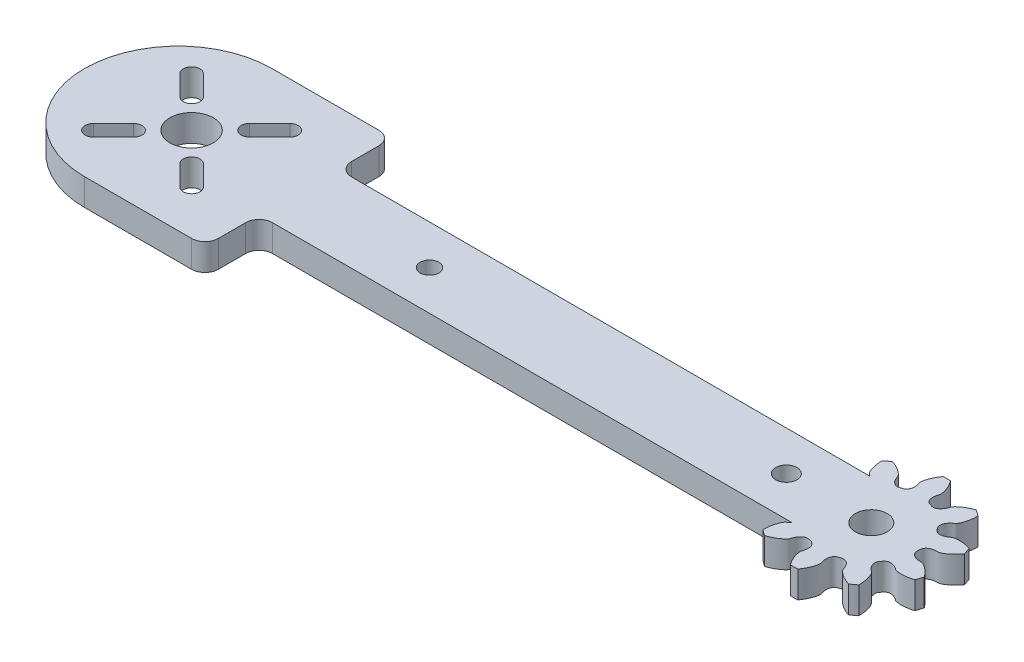
SolidWorks part; units mm, degrees
material "Thornel VCB-20 Carbon Cloth"
ref_plane "Front Plane" through (0, 0, 0) normal (0, 0, 1) x (1, 0, 0)
ref_plane "Top Plane" through (0, 0, 0) normal (0, 1, 0) x (1, 0, 0)
ref_plane "Right Plane" through (0, 0, 0) normal (1, 0, 0) x (0, 0, -1)
sketch "Sketch1" plane through (0, 0, 0) normal (0, 1, 0) x (1, 0, 0)
  line L0 (-58.0134, 7.2134) -> (-43.5866, -7.2134) construction
  line L1 (-50.8, 14) -> (-36.8, 14)
  line L2 (-50.8, 14) -> (-50.8, -14) construction
  line L3 (-50.8, -14) -> (-36.8, -14)
  line L7 (-58.4887, -7.6887) -> (-43.1113, 7.6887) construction
  line L8 (-58.1362, 7.3362) -> (-55.131, 4.331) construction
  line L9 (-57.2523, 8.2201) -> (-54.2471, 5.2149)
  line L10 (-59.0201, 6.4523) -> (-56.0149, 3.4471)
  line L11 (-43.4638, 7.3362) -> (-46.469, 4.331) construction
  line L12 (-42.5799, 6.4523) -> (-45.5851, 3.4471)
  line L13 (-44.3477, 8.2201) -> (-47.3529, 5.2149)
  line L14 (-43.4638, -7.3362) -> (-46.469, -4.331) construction
  line L15 (-44.3477, -8.2201) -> (-47.3529, -5.2149)
  line L16 (-42.5799, -6.4523) -> (-45.5851, -3.4471)
  line L17 (-58.1362, -7.3362) -> (-55.131, -4.331) construction
  line L18 (-59.0201, -6.4523) -> (-56.0149, -3.4471)
  line L19 (-57.2523, -8.2201) -> (-54.2471, -5.2149)
  line L21 (-34.8, 7.9146) -> (-34.8, 12)
  line L24 (-34.8, -12) -> (-34.8, -7.9146)
  line L32 (-32.8, 5.9146) -> (50.8, 5.9146)
  line L33 (-32.8, -5.9146) -> (50.8, -5.9146)
  line L34 (-50.8, 0) -> (50.8, 0) construction
  line L35 (-50.8, 14) -> (-52.8, 14)
  line L36 (-50.8, -14) -> (-52.8, -14)
  circle A2 centre (-50.8, 0) radius 3.25
  arc A3 (-57.2523, 8.2201) -> (-59.0201, 6.4523) centre (-58.1362, 7.3362) ccw
  arc A4 (-56.0149, 3.4471) -> (-54.2471, 5.2149) centre (-55.131, 4.331) ccw
  arc A5 (-42.5799, 6.4523) -> (-44.3477, 8.2201) centre (-43.4638, 7.3362) ccw
  arc A6 (-47.3529, 5.2149) -> (-45.5851, 3.4471) centre (-46.469, 4.331) ccw
  arc A7 (-44.3477, -8.2201) -> (-42.5799, -6.4523) centre (-43.4638, -7.3362) ccw
  arc A8 (-45.5851, -3.4471) -> (-47.3529, -5.2149) centre (-46.469, -4.331) ccw
  arc A9 (-59.0201, -6.4523) -> (-57.2523, -8.2201) centre (-58.1362, -7.3362) ccw
  arc A10 (-54.2471, -5.2149) -> (-56.0149, -3.4471) centre (-55.131, -4.331) ccw
  circle A11 centre (50.8, 0) radius 2.3813
  arc A12 (-34.8, -7.9146) -> (-32.8, -5.9146) centre (-32.8, -7.9146) cw
  arc A13 (-32.8, 5.9146) -> (-34.8, 7.9146) centre (-32.8, 7.9146) cw
  arc A14 (-36.8, -14) -> (-34.8, -12) centre (-36.8, -12) ccw
  arc A15 (-34.8, 12) -> (-36.8, 14) centre (-36.8, 12) ccw
  arc A16 (50.8, 5.9146) -> (50.8, -5.9146) centre (50.8, 0) cw
  arc A17 (-52.8, -14) -> (-52.8, 14) centre (-52.8, 0) cw
  circle A18 centre (-15.24, 0) radius 1.397
  point P0 (0, 0)
  point P12 (-50.8, 0)
  point P14 (-50.8, 0)
  point P17 (-56.6336, 5.8336)
  point P27 (-44.9664, 5.8336)
  point P34 (-44.9664, -5.8336)
  point P41 (-56.6336, -5.8336)
  point P46 (-50.8, 0)
  point P53 (-34.8, -7)
  point P56 (-34.8, 7)
  point P59 (-34.8, -14)
  point P62 (-34.8, 14)
  dimension "D3" = 6.5
  dimension "D6" = 8.25
  dimension "D10" = 4.7625
  dimension "D17" = 2
  dimension "D18" = 2
  dimension "D16" = 5.9146
  dimension "D2" = 14
  dimension "D21" = 2.794
  dimension "D22" = 66.04
  dimension "D4" = 45
  dimension "D5" = 45
  dimension "D7" = 4.25
  dimension "D8" = 2.5
  dimension "D11" = 16
  dimension "D12" = 16
  dimension "D13" = 7
  dimension "D14" = 7
  dimension "D15" = 101.6
  dimension "D19" = 50.8
  dimension "D20" = 2
  dimension "D9" = 4
extrude "Boss-Extrude1" add sketch "Sketch1" along normal blind 4
sketch "Sketch2" plane through (0, 0, 0) normal (0, -1, 0) x (1, 0, 0)
  circle A0 centre (38.1, 0) radius 1.5875
  circle A1 centre (50.8, 0) radius 2.3813 construction
  dimension "D1" = 3.175
  dimension "D2" = 12.7
extrude "Cut-Extrude1" cut sketch "Sketch2" against normal blind 10
sketch "Sketch3" plane through (0, 0, 0) normal (0, -1, 0) x (1, 0, 0)
  arc A0 (40.0686, 4.1334) -> (39.7228, 3.0691) centre (50.7532, 0.0734) ccw
  arc A1 (39.7228, -2.9222) -> (40.0686, -3.9866) centre (50.7532, 0.0734) ccw
  arc A2 (43.5902, -8.8336) -> (44.4956, -9.4915) centre (50.7532, 0.0734) ccw
  arc A3 (50.1937, -11.3429) -> (51.3128, -11.3429) centre (50.7532, 0.0734) ccw
  arc A4 (57.0109, -9.4915) -> (57.9163, -8.8336) centre (50.7532, 0.0734) ccw
  arc A5 (61.4378, -3.9866) -> (61.7837, -2.9222) centre (50.7532, 0.0734) ccw
  arc A6 (61.7837, 3.0691) -> (61.4378, 4.1334) centre (50.7532, 0.0734) ccw
  arc A7 (57.9163, 8.9805) -> (57.0109, 9.6383) centre (50.7532, 0.0734) ccw
  arc A8 (51.3128, 11.4897) -> (50.1937, 11.4897) centre (50.7532, 0.0734) ccw
  arc A9 (44.4956, 9.6383) -> (43.5902, 8.9805) centre (50.7532, 0.0734) ccw
  circle A10 centre (50.7532, 0.0734) radius 4.0735
  spline S0 degree 3 poles (39.7228, 3.0691) (39.8092, 2.9516) (39.9522, 2.7692) (40.1581, 2.5337) (40.3253, 2.3574) (40.4889, 2.1982) (40.6479, 2.0557) (40.8012, 1.929) (40.9477, 1.8176) (41.0866, 1.7206) (41.2169, 1.6373) (41.3377, 1.5668) (41.4483, 1.508) (41.5479, 1.4604) (41.6357, 1.4219) (41.7286, 1.388) (41.8483, 1.3381) (41.9663, 1.3631) (42.0573, 1.3611) (42.1051, 1.3604) (42.1524, 1.3587) (42.1991, 1.3562) (42.2901, 1.3499) (42.4086, 1.3365) (42.5525, 1.3107) (42.6765, 1.2808) (42.7956, 1.2439) (42.9096, 1.1998) (43.0187, 1.148) (43.111, 1.0946) (43.1879, 1.0422) (43.2512, 0.9929) (43.3116, 0.939) (43.3686, 0.8801) (43.4217, 0.816) (43.4703, 0.7464) (43.5135, 0.6712) (43.5502, 0.5907) (43.5794, 0.5053) (43.5966, 0.4309) (43.6057, 0.3699) (43.61, 0.3234) (43.6116, 0.2818) (43.6116, 0.1985) (43.6077, 0.0734) (43.6116, -0.0516) (43.6116, -0.135) (43.61, -0.1766) (43.6057, -0.223) (43.5966, -0.2841) (43.5794, -0.3584) (43.5502, -0.4439) (43.5135, -0.5244) (43.4703, -0.5995) (43.4217, -0.6691) (43.3686, -0.7333) (43.3116, -0.7921) (43.2512, -0.846) (43.1775, -0.9035) (43.0885, -0.9621) (42.9829, -1.0193) (42.8722, -1.0685) (42.7564, -1.1101) (42.6357, -1.1447) (42.5101, -1.1723) (42.3795, -1.1932) (42.2753, -1.2041) (42.1991, -1.2094) (42.1524, -1.2118) (42.1051, -1.2136) (42.0573, -1.2143) (41.9663, -1.2163) (41.8483, -1.1912) (41.7286, -1.2412) (41.6357, -1.2751) (41.5479, -1.3135) (41.4483, -1.3612) (41.3377, -1.4199) (41.2169, -1.4905) (41.0866, -1.5738) (40.9477, -1.6708) (40.8012, -1.7822) (40.6479, -1.9088) (40.4889, -2.0514) (40.3253, -2.2105) (40.1581, -2.3869) (39.9522, -2.6224) (39.8092, -2.8048) (39.7228, -2.9222) knots 0.011285 0.011285 0.011285 0.011285 0.051699 0.075508 0.097957 0.119044 0.138772 0.157139 0.174145 0.189791 0.204076 0.217001 0.228565 0.238769 0.247612 0.255095 0.266315 0.282698 0.287164 0.291581 0.295951 0.300274 0.304552 0.321228 0.333312 0.345077 0.356567 0.36784 0.378959 0.390003 0.397367 0.404766 0.412228 0.419785 0.427466 0.435294 0.44329 0.45146 0.4598 0.46829 0.472581 0.476895 0.481226 0.484109 0.5 0.515891 0.518774 0.523105 0.527419 0.53171 0.5402 0.54854 0.55671 0.564706 0.572534 0.580215 0.587772 0.595234 0.602633 0.613675 0.624735 0.635897 0.647236 0.658812 0.670678 0.682878 0.695448 0.699726 0.704049 0.708419 0.712836 0.717302 0.733685 0.744905 0.752388 0.761231 0.771435 0.782999 0.795924 0.810209 0.825855 0.842861 0.861228 0.880956 0.902043 0.924492 0.948301 0.988715 0.988715 0.988715 0.988715 weights 1 1 1 1 1 1 1 1 1 1 1 1 1 1 1 1 1 1 1 1 1 1 1 1 1 1 1 1 1 1 1 1 1 1 1 1 1 1 1 1 1 1 1 1 1 1 1 1 1 1 1 1 1 1 1 1 1 1 1 1 1 1 1 1 1 1 1 1 1 1 1 1 1 1 1 1 1 1 1 1 1 1 1 1 1 1 1 1 1
  spline S1 degree 3 poles (40.0686, -3.9866) (40.2075, -4.0308) (40.4305, -4.0943) (40.7354, -4.1638) (40.9743, -4.2082) (41.2003, -4.2408) (41.4127, -4.2627) (41.6112, -4.275) (41.7952, -4.279) (41.9646, -4.2758) (42.1189, -4.2667) (42.2581, -4.2527) (42.3821, -4.2353) (42.4907, -4.2153) (42.5844, -4.1947) (42.6795, -4.1676) (42.8057, -4.1376) (42.8864, -4.048) (42.9611, -3.9961) (43.0002, -3.9686) (43.0395, -3.9423) (43.0788, -3.9168) (43.1561, -3.8684) (43.2598, -3.8096) (43.3915, -3.7458) (43.5094, -3.6972) (43.6273, -3.657) (43.7456, -3.6257) (43.8642, -3.6035) (43.9703, -3.5924) (44.0634, -3.5896) (44.1435, -3.5923) (44.2241, -3.6004) (44.3048, -3.6145) (44.3855, -3.6352) (44.4657, -3.6629) (44.5448, -3.6984) (44.6218, -3.7419) (44.6957, -3.7939) (44.7533, -3.8439) (44.7965, -3.888) (44.8273, -3.923) (44.853, -3.9557) (44.902, -4.0232) (44.9724, -4.1266) (45.049, -4.2255) (45.098, -4.2929) (45.1212, -4.3275) (45.145, -4.3677) (45.1735, -4.4223) (45.2033, -4.4926) (45.2299, -4.5789) (45.2475, -4.6656) (45.2568, -4.7518) (45.2584, -4.8367) (45.2531, -4.9198) (45.2416, -5.0009) (45.2244, -5.08) (45.1985, -5.1698) (45.161, -5.2696) (45.1092, -5.3779) (45.0485, -5.4828) (44.9794, -5.5845) (44.902, -5.6834) (44.8166, -5.7796) (44.7233, -5.8732) (44.6453, -5.9433) (44.5868, -5.9924) (44.5504, -6.0218) (44.5132, -6.051) (44.4749, -6.0797) (44.4025, -6.1348) (44.2923, -6.1839) (44.2249, -6.2946) (44.1696, -6.3767) (44.1211, -6.4594) (44.0686, -6.5565) (44.0137, -6.669) (43.9574, -6.7971) (43.901, -6.9411) (43.8456, -7.1012) (43.7925, -7.2775) (43.743, -7.47) (43.6981, -7.6788) (43.6593, -7.9038) (43.6277, -8.1447) (43.5996, -8.4562) (43.5911, -8.6878) (43.5902, -8.8336) knots 0.011285 0.011285 0.011285 0.011285 0.051699 0.075508 0.097957 0.119044 0.138772 0.157139 0.174145 0.189791 0.204076 0.217001 0.228565 0.238769 0.247612 0.255095 0.266315 0.282698 0.287164 0.291581 0.295951 0.300274 0.304552 0.321228 0.333312 0.345077 0.356567 0.36784 0.378959 0.390003 0.397367 0.404766 0.412228 0.419785 0.427466 0.435294 0.44329 0.45146 0.4598 0.46829 0.472581 0.476895 0.481226 0.484109 0.5 0.515891 0.518774 0.523105 0.527419 0.53171 0.5402 0.54854 0.55671 0.564706 0.572534 0.580215 0.587772 0.595234 0.602633 0.613675 0.624735 0.635897 0.647236 0.658812 0.670678 0.682878 0.695448 0.699726 0.704049 0.708419 0.712836 0.717302 0.733685 0.744905 0.752388 0.761231 0.771435 0.782999 0.795924 0.810209 0.825855 0.842861 0.861228 0.880956 0.902043 0.924492 0.948301 0.988715 0.988715 0.988715 0.988715 weights 1 1 1 1 1 1 1 1 1 1 1 1 1 1 1 1 1 1 1 1 1 1 1 1 1 1 1 1 1 1 1 1 1 1 1 1 1 1 1 1 1 1 1 1 1 1 1 1 1 1 1 1 1 1 1 1 1 1 1 1 1 1 1 1 1 1 1 1 1 1 1 1 1 1 1 1 1 1 1 1 1 1 1 1 1 1 1 1 1
  spline S2 degree 3 poles (44.4956, -9.4915) (44.634, -9.4456) (44.8517, -9.3659) (45.1392, -9.2429) (45.3586, -9.1384) (45.5606, -9.0319) (45.7453, -8.9248) (45.9131, -8.8181) (46.0643, -8.7132) (46.1995, -8.6111) (46.319, -8.5129) (46.4234, -8.4198) (46.5135, -8.3328) (46.5896, -8.2528) (46.6532, -8.1811) (46.7142, -8.1033) (46.7987, -8.0048) (46.8113, -7.8849) (46.8413, -7.799) (46.8568, -7.7537) (46.8731, -7.7093) (46.8898, -7.6656) (46.924, -7.5811) (46.9733, -7.4725) (47.0423, -7.3436) (47.1091, -7.2349) (47.181, -7.1331) (47.2582, -7.0382) (47.3411, -6.9505) (47.4204, -6.8792) (47.4941, -6.8222) (47.5605, -6.7773) (47.6304, -6.7365) (47.704, -6.7005) (47.7815, -6.6698) (47.8627, -6.6451) (47.9475, -6.6273) (48.0354, -6.6172) (48.1257, -6.6158) (48.2017, -6.6225) (48.2626, -6.6327) (48.3081, -6.6429) (48.3481, -6.6543) (48.4274, -6.68) (48.5451, -6.7224) (48.6653, -6.7573) (48.7445, -6.7831) (48.7836, -6.7974) (48.8264, -6.8159) (48.8817, -6.8434) (48.9471, -6.8827) (49.0193, -6.9369) (49.0846, -6.9967) (49.1427, -7.061) (49.1939, -7.1287) (49.2384, -7.1991) (49.2768, -7.2715) (49.3094, -7.3455) (49.3413, -7.4334) (49.3695, -7.5362) (49.3913, -7.6543) (49.4038, -7.7748) (49.4077, -7.8977) (49.4033, -8.0232) (49.3907, -8.1512) (49.3702, -8.2818) (49.3484, -8.3844) (49.3299, -8.4585) (49.3178, -8.5037) (49.3048, -8.5492) (49.2907, -8.5949) (49.2645, -8.682) (49.2042, -8.7864) (49.2147, -8.9157) (49.2183, -9.0146) (49.2277, -9.11) (49.2422, -9.2194) (49.2639, -9.3427) (49.2937, -9.4794) (49.3327, -9.6291) (49.382, -9.7911) (49.4426, -9.9649) (49.5157, -10.1499) (49.6022, -10.3451) (49.703, -10.55) (49.819, -10.7635) (49.9794, -11.032) (50.1087, -11.2244) (50.1937, -11.3429) knots 0.011285 0.011285 0.011285 0.011285 0.051699 0.075508 0.097957 0.119044 0.138772 0.157139 0.174145 0.189791 0.204076 0.217001 0.228565 0.238769 0.247612 0.255095 0.266315 0.282698 0.287164 0.291581 0.295951 0.300274 0.304552 0.321228 0.333312 0.345077 0.356567 0.36784 0.378959 0.390003 0.397367 0.404766 0.412228 0.419785 0.427466 0.435294 0.44329 0.45146 0.4598 0.46829 0.472581 0.476895 0.481226 0.484109 0.5 0.515891 0.518774 0.523105 0.527419 0.53171 0.5402 0.54854 0.55671 0.564706 0.572534 0.580215 0.587772 0.595234 0.602633 0.613675 0.624735 0.635897 0.647236 0.658812 0.670678 0.682878 0.695448 0.699726 0.704049 0.708419 0.712836 0.717302 0.733685 0.744905 0.752388 0.761231 0.771435 0.782999 0.795924 0.810209 0.825855 0.842861 0.861228 0.880956 0.902043 0.924492 0.948301 0.988715 0.988715 0.988715 0.988715 weights 1 1 1 1 1 1 1 1 1 1 1 1 1 1 1 1 1 1 1 1 1 1 1 1 1 1 1 1 1 1 1 1 1 1 1 1 1 1 1 1 1 1 1 1 1 1 1 1 1 1 1 1 1 1 1 1 1 1 1 1 1 1 1 1 1 1 1 1 1 1 1 1 1 1 1 1 1 1 1 1 1 1 1 1 1 1 1 1 1
  spline S3 degree 3 poles (51.3128, -11.3429) (51.3978, -11.2244) (51.527, -11.032) (51.6874, -10.7635) (51.8035, -10.55) (51.9043, -10.3451) (51.9907, -10.1499) (52.0638, -9.9649) (52.1245, -9.7911) (52.1738, -9.6291) (52.2128, -9.4794) (52.2425, -9.3427) (52.2642, -9.2194) (52.2788, -9.11) (52.2882, -9.0146) (52.2917, -8.9157) (52.3022, -8.7864) (52.242, -8.682) (52.2157, -8.5949) (52.2016, -8.5492) (52.1887, -8.5037) (52.1766, -8.4585) (52.1545, -8.37) (52.1306, -8.2531) (52.1106, -8.1083) (52.1008, -7.9811) (52.0991, -7.8565) (52.1058, -7.7343) (52.1213, -7.6146) (52.1436, -7.5104) (52.1697, -7.421) (52.197, -7.3455) (52.2296, -7.2715) (52.268, -7.1991) (52.3126, -7.1287) (52.3637, -7.061) (52.4219, -6.9967) (52.4871, -6.9369) (52.5593, -6.8827) (52.6248, -6.8434) (52.68, -6.8159) (52.7229, -6.7974) (52.7619, -6.7831) (52.8412, -6.7573) (52.9613, -6.7224) (53.079, -6.68) (53.1583, -6.6543) (53.1983, -6.6429) (53.2439, -6.6327) (53.3047, -6.6225) (53.3807, -6.6158) (53.471, -6.6172) (53.559, -6.6273) (53.6438, -6.6451) (53.725, -6.6698) (53.8024, -6.7005) (53.876, -6.7365) (53.9459, -6.7773) (54.0234, -6.8297) (54.1066, -6.8962) (54.1936, -6.9789) (54.2746, -7.0691) (54.35, -7.1663) (54.4201, -7.2704) (54.4853, -7.3813) (54.5455, -7.499) (54.588, -7.5948) (54.6166, -7.6656) (54.6334, -7.7093) (54.6497, -7.7537) (54.6651, -7.799) (54.6951, -7.8849) (54.7077, -8.0048) (54.7922, -8.1033) (54.8532, -8.1811) (54.9169, -8.2528) (54.993, -8.3328) (55.083, -8.4198) (55.1875, -8.5129) (55.307, -8.6111) (55.4421, -8.7132) (55.5934, -8.8181) (55.7612, -8.9248) (55.9459, -9.0319) (56.1478, -9.1384) (56.3672, -9.2429) (56.6548, -9.3659) (56.8725, -9.4456) (57.0109, -9.4915) knots 0.011285 0.011285 0.011285 0.011285 0.051699 0.075508 0.097957 0.119044 0.138772 0.157139 0.174145 0.189791 0.204076 0.217001 0.228565 0.238769 0.247612 0.255095 0.266315 0.282698 0.287164 0.291581 0.295951 0.300274 0.304552 0.321228 0.333312 0.345077 0.356567 0.36784 0.378959 0.390003 0.397367 0.404766 0.412228 0.419785 0.427466 0.435294 0.44329 0.45146 0.4598 0.46829 0.472581 0.476895 0.481226 0.484109 0.5 0.515891 0.518774 0.523105 0.527419 0.53171 0.5402 0.54854 0.55671 0.564706 0.572534 0.580215 0.587772 0.595234 0.602633 0.613675 0.624735 0.635897 0.647236 0.658812 0.670678 0.682878 0.695448 0.699726 0.704049 0.708419 0.712836 0.717302 0.733685 0.744905 0.752388 0.761231 0.771435 0.782999 0.795924 0.810209 0.825855 0.842861 0.861228 0.880956 0.902043 0.924492 0.948301 0.988715 0.988715 0.988715 0.988715 weights 1 1 1 1 1 1 1 1 1 1 1 1 1 1 1 1 1 1 1 1 1 1 1 1 1 1 1 1 1 1 1 1 1 1 1 1 1 1 1 1 1 1 1 1 1 1 1 1 1 1 1 1 1 1 1 1 1 1 1 1 1 1 1 1 1 1 1 1 1 1 1 1 1 1 1 1 1 1 1 1 1 1 1 1 1 1 1 1 1
  spline S4 degree 3 poles (57.9163, -8.8336) (57.9154, -8.6878) (57.9068, -8.4562) (57.8788, -8.1447) (57.8471, -7.9038) (57.8083, -7.6788) (57.7635, -7.47) (57.7139, -7.2775) (57.6608, -7.1012) (57.6055, -6.9411) (57.549, -6.7971) (57.4928, -6.669) (57.4379, -6.5565) (57.3853, -6.4594) (57.3368, -6.3767) (57.2816, -6.2946) (57.2141, -6.1839) (57.1039, -6.1348) (57.0315, -6.0797) (56.9932, -6.051) (56.956, -6.0218) (56.9197, -5.9924) (56.8498, -5.9338) (56.7618, -5.8533) (56.6605, -5.7478) (56.5778, -5.6507) (56.5031, -5.5509) (56.4368, -5.4482) (56.379, -5.3422) (56.3357, -5.2448) (56.3042, -5.1571) (56.282, -5.08) (56.2649, -5.0009) (56.2534, -4.9198) (56.2481, -4.8367) (56.2497, -4.7518) (56.2589, -4.6656) (56.2765, -4.5789) (56.3031, -4.4926) (56.3329, -4.4223) (56.3615, -4.3677) (56.3852, -4.3275) (56.4084, -4.2929) (56.4574, -4.2255) (56.5341, -4.1266) (56.6044, -4.0232) (56.6534, -3.9557) (56.6791, -3.923) (56.71, -3.888) (56.7532, -3.8439) (56.8108, -3.7939) (56.8846, -3.7419) (56.9617, -3.6984) (57.0408, -3.6629) (57.121, -3.6352) (57.2017, -3.6145) (57.2824, -3.6004) (57.3629, -3.5923) (57.4564, -3.5892) (57.5628, -3.594) (57.6818, -3.6098) (57.8003, -3.6351) (57.9184, -3.6695) (58.0364, -3.7125) (58.1543, -3.7639) (58.2722, -3.8238) (58.3629, -3.8763) (58.4277, -3.9168) (58.4669, -3.9423) (58.5062, -3.9686) (58.5453, -3.9961) (58.6201, -4.048) (58.7008, -4.1376) (58.827, -4.1676) (58.9221, -4.1947) (59.0157, -4.2153) (59.1243, -4.2353) (59.2483, -4.2527) (59.3875, -4.2667) (59.5419, -4.2758) (59.7112, -4.279) (59.8953, -4.275) (60.0937, -4.2627) (60.3062, -4.2408) (60.5321, -4.2082) (60.771, -4.1638) (61.076, -4.0943) (61.2989, -4.0308) (61.4378, -3.9866) knots 0.011285 0.011285 0.011285 0.011285 0.051699 0.075508 0.097957 0.119044 0.138772 0.157139 0.174145 0.189791 0.204076 0.217001 0.228565 0.238769 0.247612 0.255095 0.266315 0.282698 0.287164 0.291581 0.295951 0.300274 0.304552 0.321228 0.333312 0.345077 0.356567 0.36784 0.378959 0.390003 0.397367 0.404766 0.412228 0.419785 0.427466 0.435294 0.44329 0.45146 0.4598 0.46829 0.472581 0.476895 0.481226 0.484109 0.5 0.515891 0.518774 0.523105 0.527419 0.53171 0.5402 0.54854 0.55671 0.564706 0.572534 0.580215 0.587772 0.595234 0.602633 0.613675 0.624735 0.635897 0.647236 0.658812 0.670678 0.682878 0.695448 0.699726 0.704049 0.708419 0.712836 0.717302 0.733685 0.744905 0.752388 0.761231 0.771435 0.782999 0.795924 0.810209 0.825855 0.842861 0.861228 0.880956 0.902043 0.924492 0.948301 0.988715 0.988715 0.988715 0.988715 weights 1 1 1 1 1 1 1 1 1 1 1 1 1 1 1 1 1 1 1 1 1 1 1 1 1 1 1 1 1 1 1 1 1 1 1 1 1 1 1 1 1 1 1 1 1 1 1 1 1 1 1 1 1 1 1 1 1 1 1 1 1 1 1 1 1 1 1 1 1 1 1 1 1 1 1 1 1 1 1 1 1 1 1 1 1 1 1 1 1
  spline S5 degree 3 poles (61.7837, -2.9222) (61.6973, -2.8048) (61.5542, -2.6224) (61.3484, -2.3869) (61.1812, -2.2105) (61.0175, -2.0514) (60.8586, -1.9088) (60.7053, -1.7822) (60.5587, -1.6708) (60.4198, -1.5738) (60.2896, -1.4905) (60.1687, -1.4199) (60.0582, -1.3612) (59.9586, -1.3135) (59.8707, -1.2751) (59.7778, -1.2412) (59.6581, -1.1912) (59.5401, -1.2163) (59.4492, -1.2143) (59.4014, -1.2136) (59.3541, -1.2118) (59.3074, -1.2094) (59.2164, -1.203) (59.0979, -1.1897) (58.9539, -1.1639) (58.8299, -1.1339) (58.7109, -1.0971) (58.5968, -1.0529) (58.4878, -1.0012) (58.3955, -0.9478) (58.3185, -0.8953) (58.2552, -0.846) (58.1949, -0.7921) (58.1379, -0.7333) (58.0847, -0.6691) (58.0361, -0.5995) (57.993, -0.5244) (57.9562, -0.4439) (57.927, -0.3584) (57.9098, -0.2841) (57.9008, -0.223) (57.8964, -0.1766) (57.8948, -0.135) (57.8949, -0.0516) (57.8988, 0.0734) (57.8949, 0.1985) (57.8948, 0.2818) (57.8964, 0.3234) (57.9008, 0.3699) (57.9098, 0.4309) (57.927, 0.5053) (57.9562, 0.5907) (57.993, 0.6712) (58.0361, 0.7464) (58.0847, 0.816) (58.1379, 0.8801) (58.1949, 0.939) (58.2552, 0.9929) (58.329, 1.0503) (58.4179, 1.109) (58.5235, 1.1662) (58.6343, 1.2153) (58.75, 1.257) (58.8707, 1.2915) (58.9963, 1.3192) (59.1269, 1.34) (59.2312, 1.3509) (59.3074, 1.3562) (59.3541, 1.3587) (59.4014, 1.3604) (59.4492, 1.3611) (59.5401, 1.3631) (59.6581, 1.3381) (59.7778, 1.388) (59.8707, 1.4219) (59.9586, 1.4604) (60.0582, 1.508) (60.1687, 1.5668) (60.2896, 1.6373) (60.4198, 1.7206) (60.5587, 1.8176) (60.7053, 1.929) (60.8586, 2.0557) (61.0175, 2.1982) (61.1812, 2.3574) (61.3484, 2.5337) (61.5542, 2.7692) (61.6973, 2.9516) (61.7837, 3.0691) knots 0.011285 0.011285 0.011285 0.011285 0.051699 0.075508 0.097957 0.119044 0.138772 0.157139 0.174145 0.189791 0.204076 0.217001 0.228565 0.238769 0.247612 0.255095 0.266315 0.282698 0.287164 0.291581 0.295951 0.300274 0.304552 0.321228 0.333312 0.345077 0.356567 0.36784 0.378959 0.390003 0.397367 0.404766 0.412228 0.419785 0.427466 0.435294 0.44329 0.45146 0.4598 0.46829 0.472581 0.476895 0.481226 0.484109 0.5 0.515891 0.518774 0.523105 0.527419 0.53171 0.5402 0.54854 0.55671 0.564706 0.572534 0.580215 0.587772 0.595234 0.602633 0.613675 0.624735 0.635897 0.647236 0.658812 0.670678 0.682878 0.695448 0.699726 0.704049 0.708419 0.712836 0.717302 0.733685 0.744905 0.752388 0.761231 0.771435 0.782999 0.795924 0.810209 0.825855 0.842861 0.861228 0.880956 0.902043 0.924492 0.948301 0.988715 0.988715 0.988715 0.988715 weights 1 1 1 1 1 1 1 1 1 1 1 1 1 1 1 1 1 1 1 1 1 1 1 1 1 1 1 1 1 1 1 1 1 1 1 1 1 1 1 1 1 1 1 1 1 1 1 1 1 1 1 1 1 1 1 1 1 1 1 1 1 1 1 1 1 1 1 1 1 1 1 1 1 1 1 1 1 1 1 1 1 1 1 1 1 1 1 1 1
  spline S6 degree 3 poles (61.4378, 4.1334) (61.2989, 4.1776) (61.076, 4.2411) (60.771, 4.3107) (60.5321, 4.3551) (60.3062, 4.3876) (60.0937, 4.4095) (59.8953, 4.4219) (59.7112, 4.4259) (59.5419, 4.4227) (59.3875, 4.4135) (59.2483, 4.3996) (59.1243, 4.3821) (59.0157, 4.3621) (58.9221, 4.3416) (58.827, 4.3144) (58.7008, 4.2845) (58.6201, 4.1949) (58.5453, 4.143) (58.5062, 4.1154) (58.4669, 4.0891) (58.4277, 4.0636) (58.3504, 4.0153) (58.2466, 3.9564) (58.115, 3.8927) (57.9971, 3.844) (57.8791, 3.8039) (57.7609, 3.7725) (57.6422, 3.7503) (57.5362, 3.7392) (57.4431, 3.7364) (57.3629, 3.7391) (57.2824, 3.7473) (57.2017, 3.7614) (57.121, 3.782) (57.0408, 3.8098) (56.9617, 3.8452) (56.8846, 3.8888) (56.8108, 3.9407) (56.7532, 3.9908) (56.71, 4.0348) (56.6791, 4.0698) (56.6534, 4.1026) (56.6044, 4.17) (56.5341, 4.2735) (56.4574, 4.3723) (56.4084, 4.4398) (56.3852, 4.4743) (56.3615, 4.5145) (56.3329, 4.5692) (56.3031, 4.6394) (56.2765, 4.7257) (56.2589, 4.8125) (56.2497, 4.8986) (56.2481, 4.9835) (56.2534, 5.0666) (56.2649, 5.1478) (56.282, 5.2268) (56.3079, 5.3167) (56.3454, 5.4164) (56.3973, 5.5247) (56.4579, 5.6296) (56.5271, 5.7313) (56.6044, 5.8302) (56.6898, 5.9264) (56.7832, 6.0201) (56.8611, 6.0901) (56.9197, 6.1392) (56.956, 6.1687) (56.9932, 6.1979) (57.0315, 6.2266) (57.1039, 6.2816) (57.2141, 6.3307) (57.2816, 6.4415) (57.3368, 6.5235) (57.3853, 6.6063) (57.4379, 6.7033) (57.4928, 6.8159) (57.549, 6.944) (57.6055, 7.0879) (57.6608, 7.248) (57.7139, 7.4243) (57.7635, 7.6168) (57.8083, 7.8256) (57.8471, 8.0506) (57.8788, 8.2915) (57.9068, 8.603) (57.9154, 8.8347) (57.9163, 8.9805) knots 0.011285 0.011285 0.011285 0.011285 0.051699 0.075508 0.097957 0.119044 0.138772 0.157139 0.174145 0.189791 0.204076 0.217001 0.228565 0.238769 0.247612 0.255095 0.266315 0.282698 0.287164 0.291581 0.295951 0.300274 0.304552 0.321228 0.333312 0.345077 0.356567 0.36784 0.378959 0.390003 0.397367 0.404766 0.412228 0.419785 0.427466 0.435294 0.44329 0.45146 0.4598 0.46829 0.472581 0.476895 0.481226 0.484109 0.5 0.515891 0.518774 0.523105 0.527419 0.53171 0.5402 0.54854 0.55671 0.564706 0.572534 0.580215 0.587772 0.595234 0.602633 0.613675 0.624735 0.635897 0.647236 0.658812 0.670678 0.682878 0.695448 0.699726 0.704049 0.708419 0.712836 0.717302 0.733685 0.744905 0.752388 0.761231 0.771435 0.782999 0.795924 0.810209 0.825855 0.842861 0.861228 0.880956 0.902043 0.924492 0.948301 0.988715 0.988715 0.988715 0.988715 weights 1 1 1 1 1 1 1 1 1 1 1 1 1 1 1 1 1 1 1 1 1 1 1 1 1 1 1 1 1 1 1 1 1 1 1 1 1 1 1 1 1 1 1 1 1 1 1 1 1 1 1 1 1 1 1 1 1 1 1 1 1 1 1 1 1 1 1 1 1 1 1 1 1 1 1 1 1 1 1 1 1 1 1 1 1 1 1 1 1
  spline S7 degree 3 poles (57.0109, 9.6383) (56.8725, 9.5924) (56.6548, 9.5127) (56.3672, 9.3897) (56.1478, 9.2852) (55.9459, 9.1788) (55.7612, 9.0716) (55.5934, 8.965) (55.4421, 8.86) (55.307, 8.7579) (55.1875, 8.6597) (55.083, 8.5666) (54.993, 8.4796) (54.9169, 8.3997) (54.8532, 8.328) (54.7922, 8.2501) (54.7077, 8.1517) (54.6951, 8.0317) (54.6651, 7.9458) (54.6497, 7.9006) (54.6334, 7.8562) (54.6166, 7.8125) (54.5825, 7.7279) (54.5332, 7.6193) (54.4641, 7.4904) (54.3973, 7.3817) (54.3255, 7.2799) (54.2483, 7.1851) (54.1653, 7.0973) (54.086, 7.0261) (54.0124, 6.9691) (53.9459, 6.9241) (53.876, 6.8834) (53.8024, 6.8473) (53.725, 6.8166) (53.6438, 6.7919) (53.559, 6.7741) (53.471, 6.764) (53.3807, 6.7627) (53.3047, 6.7693) (53.2439, 6.7796) (53.1983, 6.7897) (53.1583, 6.8011) (53.079, 6.8269) (52.9613, 6.8692) (52.8412, 6.9042) (52.7619, 6.9299) (52.7229, 6.9442) (52.68, 6.9628) (52.6248, 6.9902) (52.5593, 7.0295) (52.4871, 7.0837) (52.4219, 7.1436) (52.3637, 7.2078) (52.3126, 7.2755) (52.268, 7.3459) (52.2296, 7.4183) (52.197, 7.4924) (52.1652, 7.5803) (52.1369, 7.683) (52.1151, 7.8011) (52.1026, 7.9216) (52.0987, 8.0446) (52.1032, 8.17) (52.1157, 8.2981) (52.1362, 8.4287) (52.1581, 8.5312) (52.1766, 8.6053) (52.1887, 8.6505) (52.2016, 8.696) (52.2157, 8.7417) (52.242, 8.8288) (52.3022, 8.9333) (52.2917, 9.0625) (52.2882, 9.1614) (52.2788, 9.2568) (52.2642, 9.3663) (52.2425, 9.4896) (52.2128, 9.6263) (52.1738, 9.7759) (52.1245, 9.938) (52.0638, 10.1118) (51.9907, 10.2967) (51.9043, 10.492) (51.8035, 10.6968) (51.6874, 10.9103) (51.527, 11.1788) (51.3978, 11.3712) (51.3128, 11.4897) knots 0.011285 0.011285 0.011285 0.011285 0.051699 0.075508 0.097957 0.119044 0.138772 0.157139 0.174145 0.189791 0.204076 0.217001 0.228565 0.238769 0.247612 0.255095 0.266315 0.282698 0.287164 0.291581 0.295951 0.300274 0.304552 0.321228 0.333312 0.345077 0.356567 0.36784 0.378959 0.390003 0.397367 0.404766 0.412228 0.419785 0.427466 0.435294 0.44329 0.45146 0.4598 0.46829 0.472581 0.476895 0.481226 0.484109 0.5 0.515891 0.518774 0.523105 0.527419 0.53171 0.5402 0.54854 0.55671 0.564706 0.572534 0.580215 0.587772 0.595234 0.602633 0.613675 0.624735 0.635897 0.647236 0.658812 0.670678 0.682878 0.695448 0.699726 0.704049 0.708419 0.712836 0.717302 0.733685 0.744905 0.752388 0.761231 0.771435 0.782999 0.795924 0.810209 0.825855 0.842861 0.861228 0.880956 0.902043 0.924492 0.948301 0.988715 0.988715 0.988715 0.988715 weights 1 1 1 1 1 1 1 1 1 1 1 1 1 1 1 1 1 1 1 1 1 1 1 1 1 1 1 1 1 1 1 1 1 1 1 1 1 1 1 1 1 1 1 1 1 1 1 1 1 1 1 1 1 1 1 1 1 1 1 1 1 1 1 1 1 1 1 1 1 1 1 1 1 1 1 1 1 1 1 1 1 1 1 1 1 1 1 1 1
  spline S8 degree 3 poles (50.1937, 11.4897) (50.1087, 11.3712) (49.9794, 11.1788) (49.819, 10.9103) (49.703, 10.6968) (49.6022, 10.492) (49.5157, 10.2967) (49.4426, 10.1118) (49.382, 9.938) (49.3327, 9.7759) (49.2937, 9.6263) (49.2639, 9.4896) (49.2422, 9.3663) (49.2277, 9.2568) (49.2183, 9.1614) (49.2147, 9.0625) (49.2042, 8.9333) (49.2645, 8.8288) (49.2907, 8.7417) (49.3048, 8.696) (49.3178, 8.6505) (49.3299, 8.6053) (49.3519, 8.5168) (49.3759, 8.4) (49.3958, 8.2551) (49.4056, 8.1279) (49.4074, 8.0033) (49.4007, 7.8812) (49.3851, 7.7615) (49.3629, 7.6572) (49.3368, 7.5678) (49.3094, 7.4924) (49.2768, 7.4183) (49.2384, 7.3459) (49.1939, 7.2755) (49.1427, 7.2078) (49.0846, 7.1436) (49.0193, 7.0837) (48.9471, 7.0295) (48.8817, 6.9902) (48.8264, 6.9628) (48.7836, 6.9442) (48.7445, 6.9299) (48.6653, 6.9042) (48.5451, 6.8692) (48.4274, 6.8269) (48.3481, 6.8011) (48.3081, 6.7897) (48.2626, 6.7796) (48.2017, 6.7693) (48.1257, 6.7627) (48.0354, 6.764) (47.9475, 6.7741) (47.8627, 6.7919) (47.7815, 6.8166) (47.704, 6.8473) (47.6304, 6.8834) (47.5605, 6.9241) (47.4831, 6.9765) (47.3998, 7.043) (47.3128, 7.1258) (47.2318, 7.2159) (47.1564, 7.3131) (47.0863, 7.4172) (47.0212, 7.5281) (46.961, 7.6459) (46.9184, 7.7417) (46.8898, 7.8125) (46.8731, 7.8562) (46.8568, 7.9006) (46.8413, 7.9458) (46.8113, 8.0317) (46.7987, 8.1517) (46.7142, 8.2501) (46.6532, 8.328) (46.5896, 8.3997) (46.5135, 8.4796) (46.4234, 8.5666) (46.319, 8.6597) (46.1995, 8.7579) (46.0643, 8.86) (45.9131, 8.965) (45.7453, 9.0716) (45.5606, 9.1788) (45.3586, 9.2852) (45.1392, 9.3897) (44.8517, 9.5127) (44.634, 9.5924) (44.4956, 9.6383) knots 0.011285 0.011285 0.011285 0.011285 0.051699 0.075508 0.097957 0.119044 0.138772 0.157139 0.174145 0.189791 0.204076 0.217001 0.228565 0.238769 0.247612 0.255095 0.266315 0.282698 0.287164 0.291581 0.295951 0.300274 0.304552 0.321228 0.333312 0.345077 0.356567 0.36784 0.378959 0.390003 0.397367 0.404766 0.412228 0.419785 0.427466 0.435294 0.44329 0.45146 0.4598 0.46829 0.472581 0.476895 0.481226 0.484109 0.5 0.515891 0.518774 0.523105 0.527419 0.53171 0.5402 0.54854 0.55671 0.564706 0.572534 0.580215 0.587772 0.595234 0.602633 0.613675 0.624735 0.635897 0.647236 0.658812 0.670678 0.682878 0.695448 0.699726 0.704049 0.708419 0.712836 0.717302 0.733685 0.744905 0.752388 0.761231 0.771435 0.782999 0.795924 0.810209 0.825855 0.842861 0.861228 0.880956 0.902043 0.924492 0.948301 0.988715 0.988715 0.988715 0.988715 weights 1 1 1 1 1 1 1 1 1 1 1 1 1 1 1 1 1 1 1 1 1 1 1 1 1 1 1 1 1 1 1 1 1 1 1 1 1 1 1 1 1 1 1 1 1 1 1 1 1 1 1 1 1 1 1 1 1 1 1 1 1 1 1 1 1 1 1 1 1 1 1 1 1 1 1 1 1 1 1 1 1 1 1 1 1 1 1 1 1
  spline S9 degree 3 poles (43.5902, 8.9805) (43.5911, 8.8347) (43.5996, 8.603) (43.6277, 8.2915) (43.6593, 8.0506) (43.6981, 7.8256) (43.743, 7.6168) (43.7925, 7.4243) (43.8456, 7.248) (43.901, 7.0879) (43.9574, 6.944) (44.0137, 6.8159) (44.0686, 6.7033) (44.1211, 6.6063) (44.1696, 6.5235) (44.2249, 6.4415) (44.2923, 6.3307) (44.4025, 6.2816) (44.4749, 6.2266) (44.5132, 6.1979) (44.5504, 6.1687) (44.5868, 6.1392) (44.6567, 6.0806) (44.7447, 6.0002) (44.846, 5.8947) (44.9287, 5.7976) (45.0033, 5.6978) (45.0697, 5.595) (45.1275, 5.489) (45.1708, 5.3916) (45.2022, 5.3039) (45.2244, 5.2268) (45.2416, 5.1478) (45.2531, 5.0666) (45.2584, 4.9835) (45.2568, 4.8986) (45.2475, 4.8125) (45.2299, 4.7257) (45.2033, 4.6394) (45.1735, 4.5692) (45.145, 4.5145) (45.1212, 4.4743) (45.098, 4.4398) (45.049, 4.3723) (44.9724, 4.2735) (44.902, 4.17) (44.853, 4.1026) (44.8273, 4.0698) (44.7965, 4.0348) (44.7533, 3.9908) (44.6957, 3.9407) (44.6218, 3.8888) (44.5448, 3.8452) (44.4657, 3.8098) (44.3855, 3.782) (44.3048, 3.7614) (44.2241, 3.7473) (44.1435, 3.7391) (44.0501, 3.736) (43.9437, 3.7409) (43.8246, 3.7567) (43.7061, 3.782) (43.588, 3.8163) (43.4701, 3.8593) (43.3522, 3.9108) (43.2343, 3.9706) (43.1435, 4.0231) (43.0788, 4.0636) (43.0395, 4.0891) (43.0002, 4.1154) (42.9611, 4.143) (42.8864, 4.1949) (42.8057, 4.2845) (42.6795, 4.3144) (42.5844, 4.3416) (42.4907, 4.3621) (42.3821, 4.3821) (42.2581, 4.3996) (42.1189, 4.4135) (41.9646, 4.4227) (41.7952, 4.4259) (41.6112, 4.4219) (41.4127, 4.4095) (41.2003, 4.3876) (40.9743, 4.3551) (40.7354, 4.3107) (40.4305, 4.2411) (40.2075, 4.1776) (40.0686, 4.1334) knots 0.011285 0.011285 0.011285 0.011285 0.051699 0.075508 0.097957 0.119044 0.138772 0.157139 0.174145 0.189791 0.204076 0.217001 0.228565 0.238769 0.247612 0.255095 0.266315 0.282698 0.287164 0.291581 0.295951 0.300274 0.304552 0.321228 0.333312 0.345077 0.356567 0.36784 0.378959 0.390003 0.397367 0.404766 0.412228 0.419785 0.427466 0.435294 0.44329 0.45146 0.4598 0.46829 0.472581 0.476895 0.481226 0.484109 0.5 0.515891 0.518774 0.523105 0.527419 0.53171 0.5402 0.54854 0.55671 0.564706 0.572534 0.580215 0.587772 0.595234 0.602633 0.613675 0.624735 0.635897 0.647236 0.658812 0.670678 0.682878 0.695448 0.699726 0.704049 0.708419 0.712836 0.717302 0.733685 0.744905 0.752388 0.761231 0.771435 0.782999 0.795924 0.810209 0.825855 0.842861 0.861228 0.880956 0.902043 0.924492 0.948301 0.988715 0.988715 0.988715 0.988715 weights 1 1 1 1 1 1 1 1 1 1 1 1 1 1 1 1 1 1 1 1 1 1 1 1 1 1 1 1 1 1 1 1 1 1 1 1 1 1 1 1 1 1 1 1 1 1 1 1 1 1 1 1 1 1 1 1 1 1 1 1 1 1 1 1 1 1 1 1 1 1 1 1 1 1 1 1 1 1 1 1 1 1 1 1 1 1 1 1 1
extrude "Boss-Extrude2" add sketch "Sketch3" against normal blind 4
